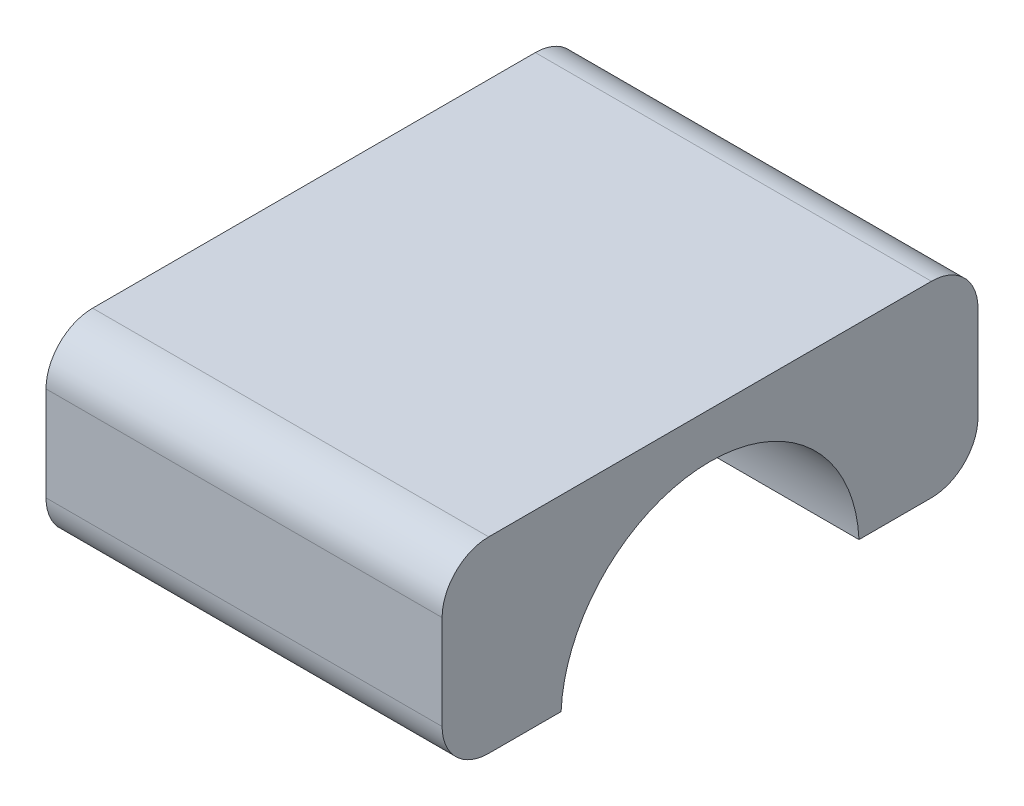
SolidWorks part; units mm, degrees
ref_plane "Front Plane" through (0, 0, 0) normal (0, 0, 1) x (1, 0, 0)
ref_plane "Top Plane" through (0, 0, 0) normal (0, 1, 0) x (1, 0, 0)
ref_plane "Right Plane" through (0, 0, 0) normal (1, 0, 0) x (0, 0, -1)
sketch "Sketch1" plane through (0, 0, 0) normal (1, 0, 0) x (0, 0, -1)
  line L0 (-19, 0.6) -> (19, 0.6)
  line L1 (23, 4.6) -> (23, 12.7)
  line L2 (19, 16.7) -> (-19, 16.7)
  line L3 (-23, 12.7) -> (-23, 4.6)
  arc A0 (19, 0.6) -> (23, 4.6) centre (19, 4.6) ccw
  arc A1 (23, 12.7) -> (19, 16.7) centre (19, 12.7) ccw
  arc A2 (-19, 16.7) -> (-23, 12.7) centre (-19, 12.7) ccw
  arc A3 (-23, 4.6) -> (-19, 0.6) centre (-19, 4.6) ccw
extrude "Boss-Extrude1" add sketch "Sketch1" along normal mid plane 34
sketch "Sketch2" plane through (0, 0, 0) normal (1, 0, 0) x (0, 0, -1)
  circle A0 centre (0, 0) radius 12.8
extrude "Cut-Extrude1" cut sketch "Sketch2" against normal through all and the other way through all
ref_plane "Plane1" through (0, 0.6, 0) normal (0, 1, 0) x (1, 0, 0)
sketch "Sketch3" plane through (0, 0.6, 0) normal (0, 1, 0) x (1, 0, 0)
  circle A0 centre (12, -17.5) radius 2
  circle A1 centre (12, 17.5) radius 2
  circle A2 centre (-12, -17.5) radius 2
  circle A3 centre (-12, 17.5) radius 2
extrude "Cut-Extrude2" cut sketch "Sketch3" along normal blind 7.5
